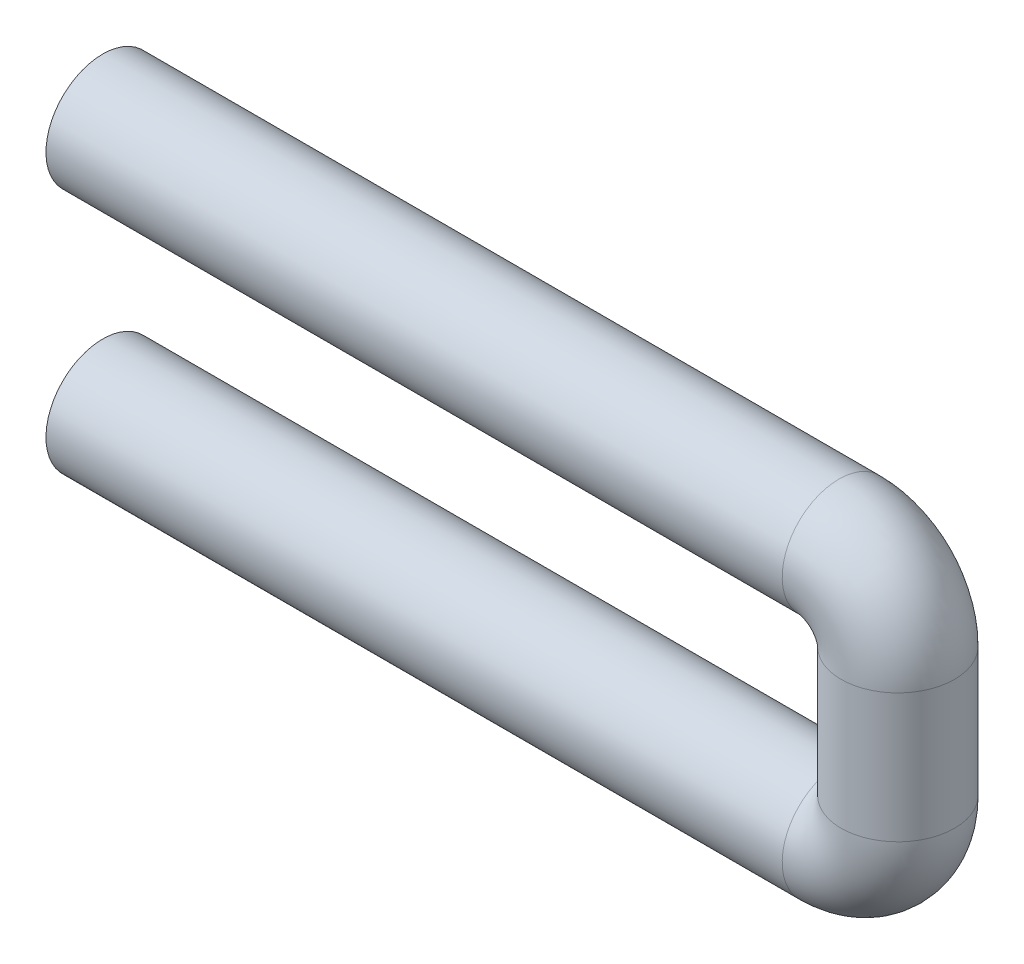
SolidWorks part; units mm, degrees
ref_plane "Ön Düzlem" through (0, 0, 0) normal (0, 0, 1) x (1, 0, 0)
ref_plane "Üst Düzlem" through (0, 0, 0) normal (0, 1, 0) x (1, 0, 0)
ref_plane "Sağ Düzlem" through (0, 0, 0) normal (1, 0, 0) x (0, 0, -1)
sketch "Çizim1" plane through (0, 0, 0) normal (0, 0, 1) x (1, 0, 0)
  line L3 (10.3845, -9.5877) -> (-6.4855, -9.5877)
  line L4 (11.7345, -5.2831) -> (11.7345, -8.2377)
  line L5 (-6.4855, -3.9331) -> (10.3845, -3.9331)
  arc A2 (10.3845, -9.5877) -> (11.7345, -8.2377) centre (10.3845, -8.2377) ccw
  arc A3 (11.7345, -5.2831) -> (10.3845, -3.9331) centre (10.3845, -5.2831) ccw
ref_plane "Düzlem1" through (-6.4855, -9.5877, 0) normal (-1, 0, 0) x (0, 0, 1)
sketch "Çizim3" plane through (-6.4855, -9.5877, 0) normal (-1, 0, 0) x (0, 0, 1)
  circle A1 centre (0, 0) radius 1.3
sweep "Süpür1" add profiles "Çizim3" path "Çizim1"
